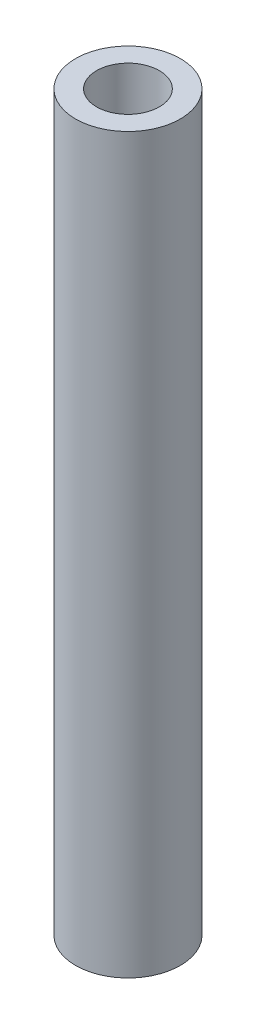
SolidWorks part; units mm, degrees
ref_plane "Front Plane" through (0, 0, 0) normal (0, 0, 1) x (1, 0, 0)
ref_plane "Top Plane" through (0, 0, 0) normal (0, 1, 0) x (1, 0, 0)
ref_plane "Right Plane" through (0, 0, 0) normal (1, 0, 0) x (0, 0, -1)
sketch "Sketch1" plane through (0, 0, 0) normal (0, 1, 0) x (1, 0, 0)
  circle A0 centre (0, 0) radius 1.5
  circle A1 centre (0, 0) radius 2.5
  dimension "D1" = 3
  dimension "D2" = 5
extrude "Boss-Extrude1" add sketch "Sketch1" along normal blind 35
